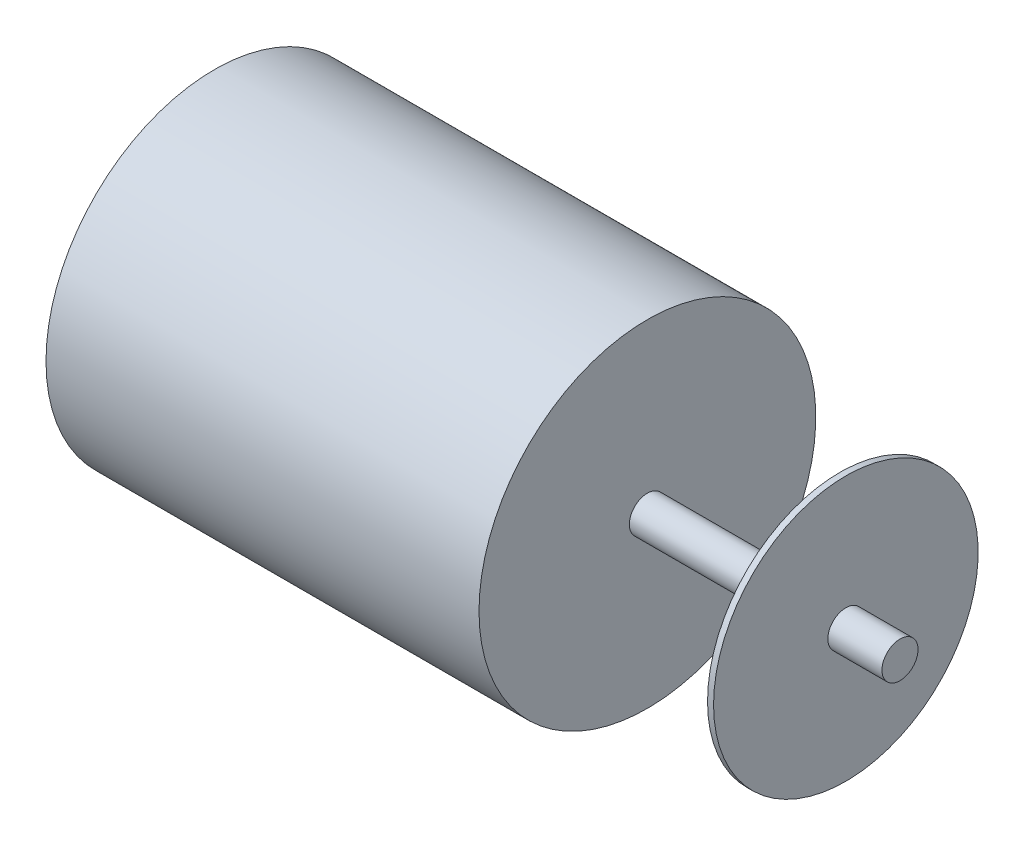
SolidWorks part; units mm, degrees
ref_plane "Front Plane" through (0, 0, 0) normal (0, 0, 1) x (1, 0, 0)
ref_plane "Top Plane" through (0, 0, 0) normal (0, 1, 0) x (1, 0, 0)
ref_plane "Right Plane" through (0, 0, 0) normal (1, 0, 0) x (0, 0, -1)
sketch "Sketch3" plane through (0, 0, 0) normal (0, 0, 1) x (1, 0, 0)
  line L0 (0, 0) -> (57, 0)
  line L1 (57, 0) -> (57, 1.5)
  line L2 (57, 1.5) -> (52.5, 1.5)
  line L3 (52.5, 1.5) -> (52.5, 11)
  line L4 (52.5, 11) -> (52, 11)
  line L5 (52, 11) -> (52, 1.5)
  line L6 (52, 1.5) -> (36, 1.5)
  line L7 (36, 1.5) -> (36, 14)
  line L8 (36, 14) -> (0, 14)
  line L9 (0, 14) -> (0, 0)
  dimension "D1" = 14
  dimension "D2" = 36
  dimension "D3" = 16
  dimension "D4" = 0.5
  dimension "D5" = 11
  dimension "D6" = 1.5
  dimension "D7" = 1.5
  dimension "D8" = 21
revolve "Revolve1" add sketch "Sketch3" angle 360 about L0
